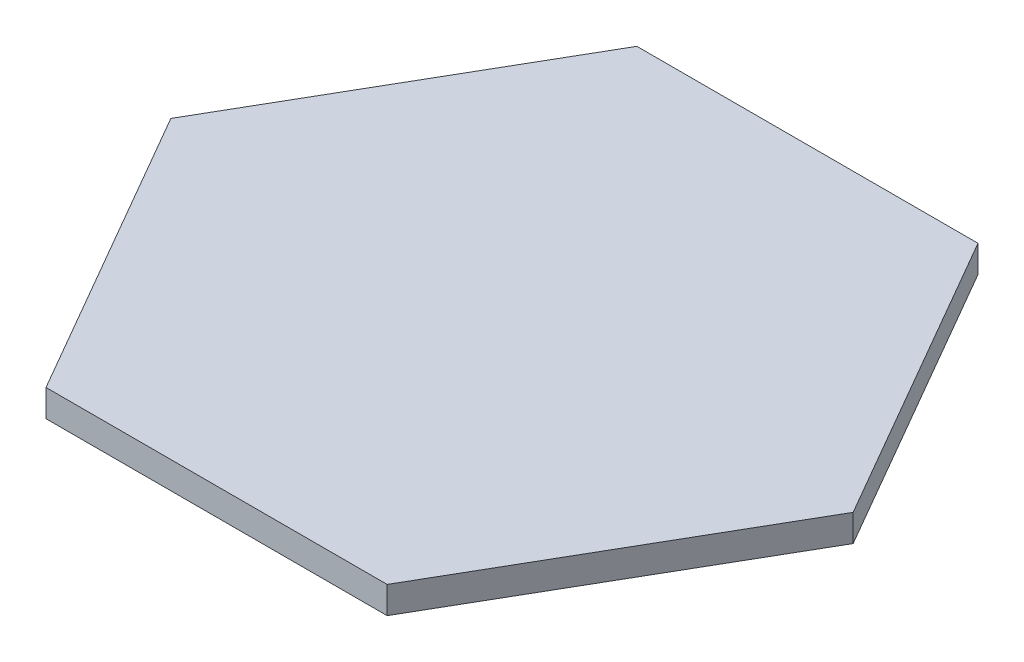
SolidWorks part; units mm, degrees
ref_plane "Front Plane" through (0, 0, 0) normal (0, 0, 1) x (1, 0, 0)
ref_plane "Top Plane" through (0, 0, 0) normal (0, 1, 0) x (1, 0, 0)
ref_plane "Right Plane" through (0, 0, 0) normal (1, 0, 0) x (0, 0, -1)
sketch "Sketch2" plane through (0, 0, 0) normal (0, 1, 0) x (1, 0, 0)
  line L0 (-80, 0) -> (-40, -69.282)
  line L1 (80, 0) -> (40, 69.282)
  line L2 (-40, 69.282) -> (-80, 0)
  line L3 (-40, -69.282) -> (40, -69.282)
  line L4 (40, -69.282) -> (80, 0)
  line L5 (-40, 69.282) -> (40, 69.282)
  circle A0 centre (0, 0) radius 69.282 construction
  dimension "D1" = 80
  dimension "D2" = 80
extrude "Boss-Extrude1" add sketch "Sketch2" along normal blind 6.35
